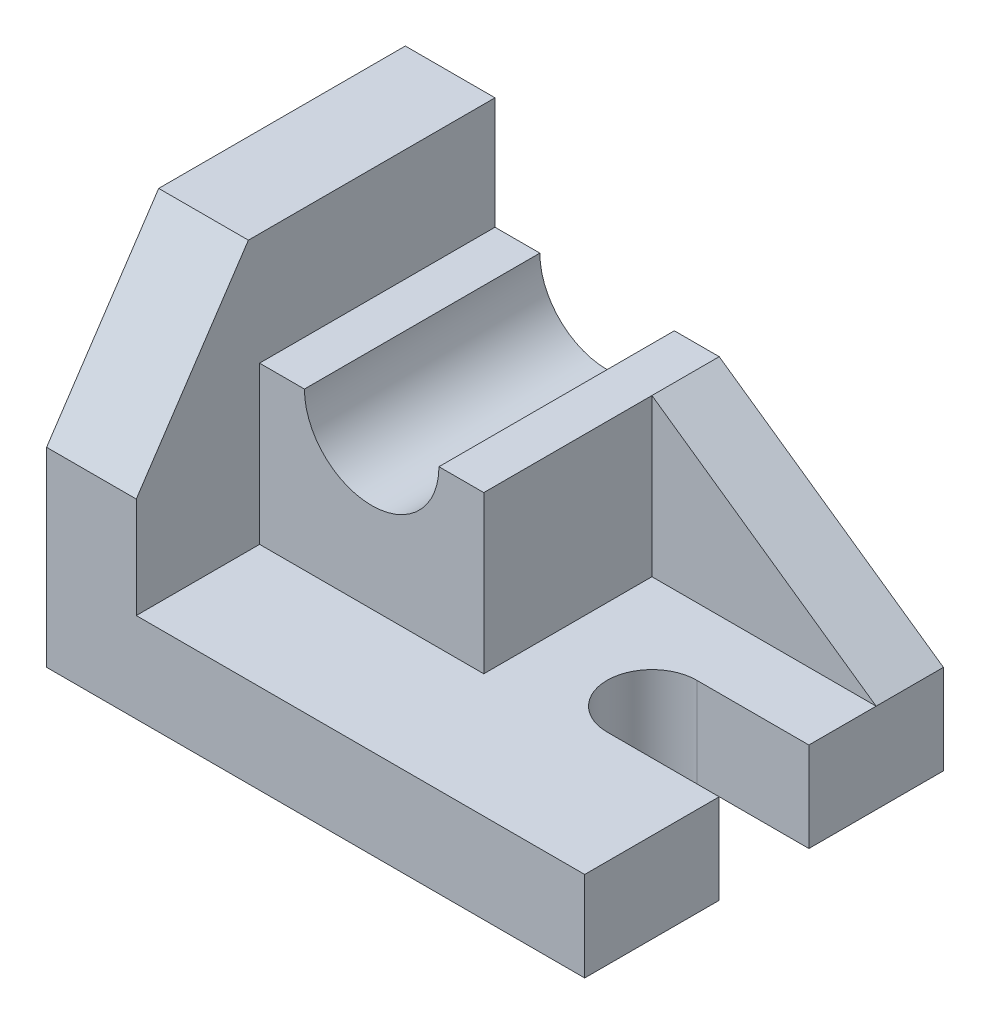
SolidWorks part; units mm, degrees
ref_plane "Front Plane" through (0, 0, 0) normal (0, 0, 1) x (1, 0, 0)
ref_plane "Top Plane" through (0, 0, 0) normal (0, 1, 0) x (1, 0, 0)
ref_plane "Right Plane" through (0, 0, 0) normal (1, 0, 0) x (0, 0, -1)
sketch "Sketch1" plane through (0, 0, 0) normal (0, 1, 0) x (1, 0, 0)
  line L0 (1930.4, 1016) -> (2438.4, 1016)
  line L1 (0, 0) -> (2438.4, 0)
  line L2 (0, 0) -> (0, 1625.6)
  line L3 (0, 1625.6) -> (2438.4, 1625.6)
  line L4 (2438.4, 0) -> (2438.4, 609.6)
  line L5 (1930.4, 609.6) -> (2438.4, 609.6)
  line L6 (2438.4, 1016) -> (2438.4, 1625.6)
  arc A0 (1930.4, 1016) -> (1930.4, 609.6) centre (1930.4, 812.8) ccw
  dimension "D1" = 2438.4
  dimension "D2" = 1625.6
  dimension "D3" = 1016
  dimension "D4" = 609.6
  dimension "D5" = 508
extrude "Boss-Extrude1" add sketch "Sketch1" along normal blind 406.4
sketch "Sketch2" plane through (0, 406.4, 0) normal (0, 1, 0) x (1, 0, 0)
  line L0 (0, 0) -> (2438.4, 0) construction
  line L1 (0, 1625.6) -> (406.4, 1625.6)
  line L2 (0, 1625.6) -> (0, 0)
  line L3 (0, 0) -> (406.4, 0)
  line L4 (406.4, 1625.6) -> (406.4, 0)
  dimension "D1" = 406.4
extrude "Boss-Extrude2" add sketch "Sketch2" along normal blind 1219.2
sketch "Sketch3" plane through (406.4, 0, 0) normal (1, 0, 0) x (0, 0, -1)
  line L0 (508, 1625.6) -> (1625.6, 1625.6)
  line L1 (0, 1625.6) -> (1625.6, 1625.6) construction
  line L2 (0, 0) -> (0, 863.6)
  line L3 (0, 1625.6) -> (0, 406.4) construction
  line L4 (0, 863.6) -> (508, 1625.6)
  line M5 (1625.6, 1625.6) -> (0, 1625.6)
  line M6 (0, 1625.6) -> (0, 406.4)
  dimension "D1" = 863.6
  dimension "D2" = 1117.6
extrude "Cut-Extrude1" cut sketch "Sketch3" against normal blind 1219.2 and the other way through all contours L4 M6 M5
sketch "Sketch4" plane through (0, 406.4, 0) normal (0, 1, 0) x (1, 0, 0)
  line L0 (2438.4, 1016) -> (2438.4, 1625.6) construction
  line L1 (406.4, 1625.6) -> (1422.4, 1625.6)
  line L2 (406.4, 1625.6) -> (406.4, 558.8)
  line L3 (406.4, 558.8) -> (1422.4, 558.8)
  line L4 (1422.4, 1625.6) -> (1422.4, 558.8)
  line L5 (1422.4, 1625.6) -> (2438.4, 1625.6)
  line L6 (1422.4, 1625.6) -> (1422.4, 1320.8)
  line L7 (1422.4, 1320.8) -> (2438.4, 1320.8)
  line L8 (2438.4, 1625.6) -> (2438.4, 1320.8)
  line M7 (406.4, 1625.6) -> (406.4, 0)
  line M13 (2438.4, 1016) -> (2438.4, 1625.6)
  line M14 (2438.4, 1625.6) -> (406.4, 1625.6)
  dimension "D1" = 1066.8
  dimension "D2" = 1016
  dimension "D3" = 304.8
extrude "Boss-Extrude3" add sketch "Sketch4" along normal blind 711.2 contours L4 L3 M14 M7 | L4 L7 M13 M14
sketch "Sketch5" plane through (0, 0, -558.8) normal (0, 0, 1) x (1, 0, 0)
  line L5 (2438.4, 1117.6) -> (2438.4, 406.4) construction
  line L10 (406.4, 406.4) -> (1422.4, 406.4) construction
  circle A0 centre (914.4, 1117.6) radius 304.8
  point P6 (0, 0)
  point P7 (1021.5531, 406.4)
  point P8 (993.3178, 406.4)
  point P11 (918.3459, 406.4)
  point P12 (2438.2368, 406.4)
  point P13 (0, 0)
  point P14 (2438.3978, 406.4)
  point P15 (0, 0)
  point P16 (1422.4, 406.4)
  point P17 (0, 0)
  dimension "D1" = 609.6
  dimension "D2" = 1524
  dimension "D3" = 711.2
extrude "Cut-Extrude2" cut sketch "Sketch5" against normal through all
sketch "Sketch6" plane through (0, 0, -1320.8) normal (0, 0, 1) x (1, 0, 0)
  line L0 (1422.4, 1117.6) -> (1422.4, 406.4)
  line L1 (1422.4, 406.4) -> (2438.4, 406.4)
  line L2 (2438.4, 406.4) -> (1422.4, 1117.6)
  line M2 (2438.4, 406.4) -> (2438.4, 1117.6)
  line M3 (2438.4, 1117.6) -> (1422.4, 1117.6)
extrude "Cut-Extrude3" cut sketch "Sketch6" against normal blind 711.2 contours L2 M2 M3
scale "Scale1" scale about centroid uniform scaling yes scale factor 0.03937
